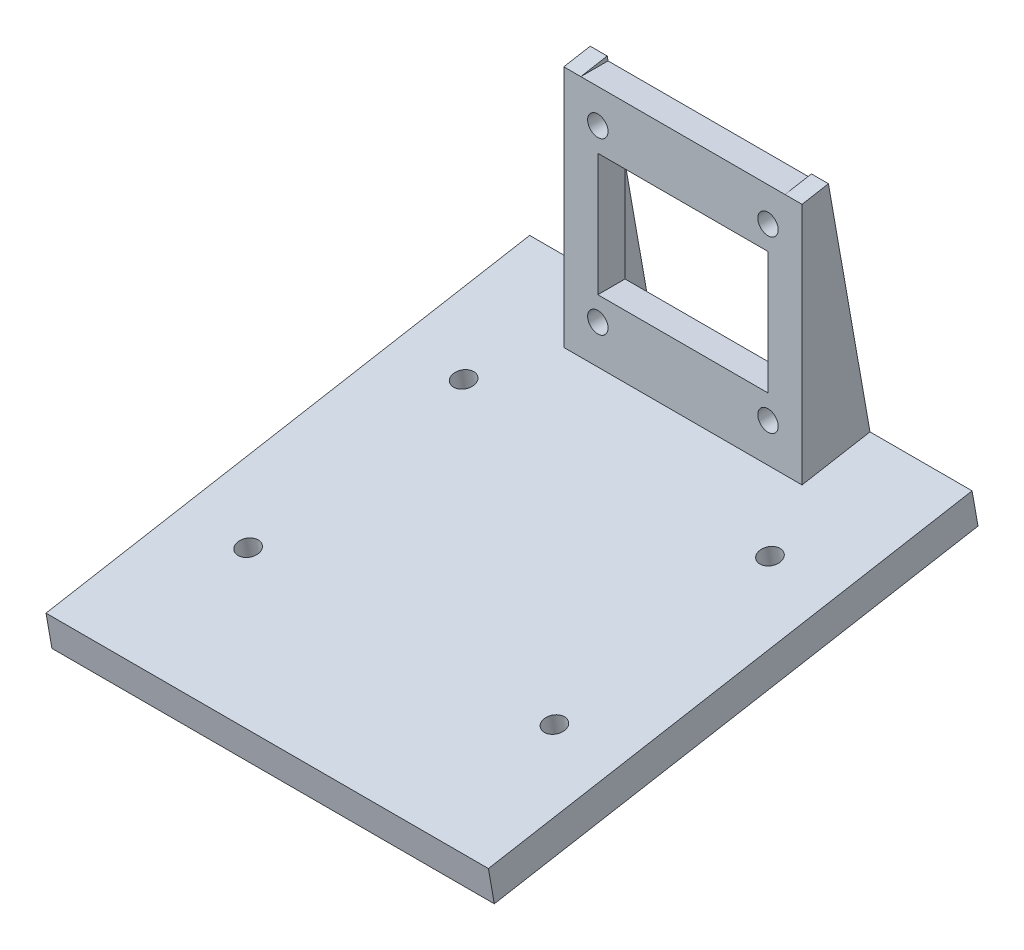
SolidWorks part; units mm, degrees
ref_plane "前视基准面" through (0, 0, 0) normal (0, 0, 1) x (1, 0, 0)
ref_plane "上视基准面" through (0, 0, 0) normal (0, 1, 0) x (1, 0, 0)
ref_plane "右视基准面" through (0, 0, 0) normal (1, 0, 0) x (0, 0, -1)
sketch "草图1" plane through (0, 0, 0) normal (0, 0, 1) x (1, 0, 0)
  line L0 (17.5, 0) -> (17.5, -35) construction
  line L1 (0, 0) -> (35, 0)
  line L2 (0, 0) -> (0, -35)
  line L3 (0, -35) -> (35, -35)
  line L4 (35, 0) -> (35, -35)
  line L5 (5, -17.5) -> (17.5, -17.5) construction
  line L6 (30, -30) -> (5, -30) construction
  line L7 (30, -30) -> (30, -5) construction
  line L8 (30, -5) -> (5, -5) construction
  line L9 (5, -30) -> (5, -5) construction
  line L10 (30, -30) -> (5, -5) construction
  line L11 (30, -5) -> (5, -30) construction
  line L13 (5, -26.5) -> (30, -26.5)
  line L14 (5, -26.5) -> (5, -8.5)
  line L15 (5, -8.5) -> (30, -8.5)
  line L16 (30, -26.5) -> (30, -8.5)
  line L17 (5, -26.5) -> (30, -8.5) construction
  line L18 (5, -8.5) -> (30, -26.5) construction
  circle A0 centre (5, -5) radius 1.5
  circle A1 centre (30, -30) radius 1.5
  circle A2 centre (30, -5) radius 1.5
  circle A3 centre (5, -30) radius 1.5
  point P7 (17.5, -17.5)
  dimension "D5" = 3
  dimension "D1" = 35
  dimension "D2" = 35
  dimension "D3" = 25
  dimension "D4" = 25
  dimension "D6" = 18
  dimension "D7" = 8.5
extrude "凸台-拉伸1" add sketch "草图1" along normal blind 4
sketch "草图2" plane through (0, 0, 0) normal (-1, 0, 0) x (0, 0, 1)
  line L0 (0, -35) -> (-5.9854, -33.9446) construction
  line L1 (-5.9854, -33.9446) -> (0, 0) construction
  line L2 (0, 0) -> (0, -35) construction
  dimension "D1" = 80
ref_plane "基准面4" through (0, -33.9446, -5.9854) normal (0, -0.9848, -0.1736) x (-1, 0, 0)
sketch "草图3" plane through (0, -33.9446, -5.9854) normal (0, -0.9848, -0.1736) x (-1, 0, 0)
  line L0 (0, -6.0777) -> (-35, -6.0777) construction
  line L1 (-35, 0) -> (-32.5, 0)
  line L3 (-35, -6.0777) -> (-32.5, -6.0777)
  line L5 (-35, 0) -> (-35, -6.0777)
  line L7 (0, 0) -> (0, -6.0777)
  line L12 (-32.5, 0) -> (-32.5, -6.0777)
  line L14 (0, 0) -> (-2.5, 0)
  line L16 (0, -6.0777) -> (-2.5, -6.0777)
  line L17 (-2.5, 0) -> (-2.5, -6.0777)
  dimension "D2" = 2.5
  dimension "D3" = 2.5
extrude "凸台-拉伸2" add sketch "草图3" against normal through all
sketch "草图4" plane through (35, 0, 0) normal (1, 0, 0) x (0, 0, -1)
  line L3 (-4, 0) -> (-6.106, -0.3713)
  line L4 (-4, -12.3149) -> (-4, 0)
  line L5 (-6.106, -0.3713) -> (-4, -12.3149)
  line L6 (-4, 0) -> (-6.106, -0.3713)
  line L7 (-4, -12.3149) -> (-4, 0)
  line L8 (-6.106, -0.3713) -> (-4, -12.3149)
  dimension "D1" = 0
extrude "切除-拉伸1" cut sketch "草图4" against normal up to surface (35 mm away) up to face at (0, -19.3245, 1.3735)
sketch "草图5" plane through (0, -33.9446, -5.9854) normal (0, -0.9848, -0.1736) x (-1, 0, 0)
  line L0 (-17.5, -6.0777) -> (-17.5, -36.0777) construction
  line L1 (-2.5, -6.0777) -> (-32.5, -6.0777) construction
  line L2 (15, -72.1554) -> (15, 0)
  line L3 (15, -72.1554) -> (-50, -72.1554)
  line L4 (15, 0) -> (-50, 0)
  line L5 (-50, -72.1554) -> (-50, 0)
  line L6 (15, -72.1554) -> (-50, 0) construction
  line L7 (15, 0) -> (-50, -72.1554) construction
  line L8 (-32.5, 0) -> (-35, 0) construction
  dimension "D1" = 65
  dimension "D2" = 30
extrude "凸台-拉伸3" add sketch "草图5" along normal blind 5 separate body
sketch "草图6" plane through (0, 0, 0) normal (-1, 0, 0) x (0, 0, 1)
  line L0 (4, -35) -> (4, -35.7053)
  line L1 (65.0738, -46.4743) -> (-5.9854, -33.9446) construction
  line L2 (4, -35.7053) -> (0, -35)
  line L3 (0, -35) -> (4, -35)
extrude "凸台-拉伸4" add sketch "草图6" against normal up to surface (35 mm away) up to face at (35, -20.6521, 0.4271)
sketch "草图7" plane through (0, -33.9446, -5.9854) normal (0, 0.9848, 0.1736) x (1, 0, 0)
  line L0 (-15, -20) -> (-5, -20) construction
  line L1 (-15, -72.1554) -> (-15, 0) construction
  line L2 (-15, 0) -> (0, 0) construction
  line L3 (17.5, -72.1554) -> (17.5, -52.86) construction
  line L4 (50, -72.1554) -> (-15, -72.1554) construction
  line L5 (-15, -52.1554) -> (-5, -52.1554) construction
  circle A0 centre (-5, -20) radius 1.5
  circle A1 centre (-5, -52.1554) radius 1.5
  circle A2 centre (40, -52.1554) radius 1.5
  circle A3 centre (40, -20) radius 1.5
  dimension "D5" = 3
  dimension "D6" = 3
  dimension "D1" = 20
  dimension "D2" = 10
  dimension "D3" = 20
  dimension "D4" = 10
extrude "切除-拉伸2" cut sketch "草图7" against normal up to surface (5 mm away) up to face at (17.5, -45.1335, 28.676)
